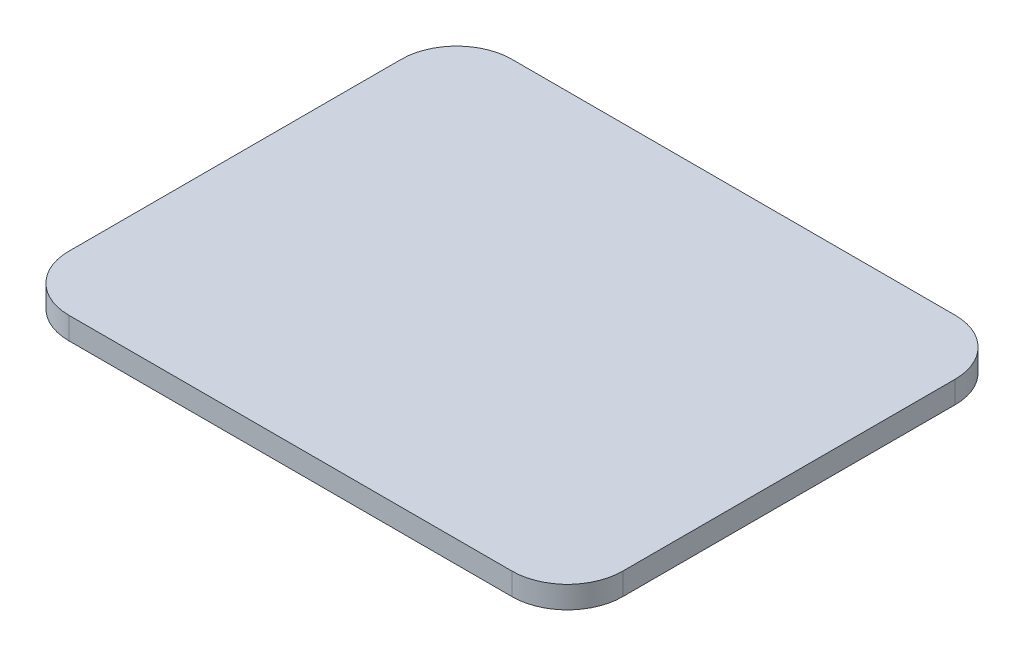
SolidWorks part; units mm, degrees
ref_plane "Front Plane" through (0, 0, 0) normal (0, 0, 1) x (1, 0, 0)
ref_plane "Top Plane" through (0, 0, 0) normal (0, 1, 0) x (1, 0, 0)
ref_plane "Right Plane" through (0, 0, 0) normal (1, 0, 0) x (0, 0, -1)
sketch "Sketch1" plane through (0, 0, 0) normal (0, 1, 0) x (1, 0, 0)
  line L1 (-250, -200) -> (250, -200)
  line L2 (-250, -200) -> (-250, 200)
  line L3 (-250, 200) -> (250, 200)
  line L4 (250, -200) -> (250, 200)
  line L5 (-250, -200) -> (250, 200) construction
  line L6 (-250, 200) -> (250, -200) construction
  point P0 (0, 0)
  dimension "D1" = 400
  dimension "D2" = 500
extrude "Boss-Extrude1" add sketch "Sketch1" along normal blind 20
fillet "Fillet1" radius 50 4 edges at (-250, 10, -200) (-250, 10, 200) (250, 10, -200) (250, 10, 200)
